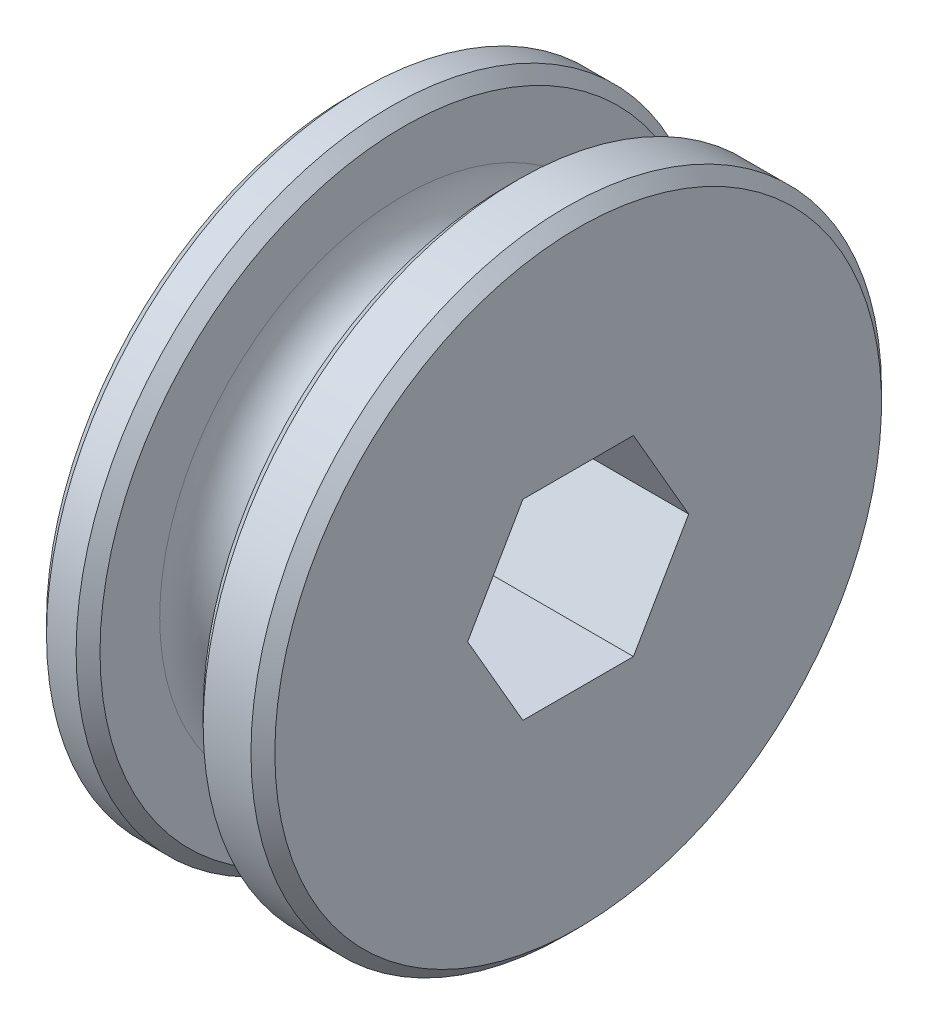
SolidWorks part; units mm, degrees
material "PET"
ref_plane "Front Plane" through (0, 0, 0) normal (0, 0, 1) x (1, 0, 0)
ref_plane "Top Plane" through (0, 0, 0) normal (0, 1, 0) x (1, 0, 0)
ref_plane "Right Plane" through (0, 0, 0) normal (1, 0, 0) x (0, 0, -1)
sketch "Sketch1" plane through (0, 0, 0) normal (0, 0, 1) x (1, 0, 0)
  line L0 (15.1765, 0) -> (0, 0)
  line L1 (0, 0) -> (15.1765, 0) construction
  line L2 (0, 0) -> (0, 20.955)
  line L3 (0, 20.955) -> (3.556, 20.955)
  line L4 (3.556, 16.1925) -> (3.556, 20.955)
  line L6 (10.414, 16.1925) -> (10.414, 20.955)
  line L7 (10.414, 20.955) -> (15.1765, 20.955)
  line L8 (15.1765, 0) -> (15.1765, 20.955)
  line L9 (6.985, 12.7635) -> (6.985, 0) construction
  arc A0 (3.556, 16.1925) -> (10.414, 16.1925) centre (6.985, 16.1925) ccw
  dimension "D1" = 3.429
  dimension "D2" = 4.7625
  dimension "D3" = 20.955
  dimension "D4" = 4.7625
  dimension "D5" = 3.556
  dimension "D7" = 12.7635
revolve "Revolve1" add sketch "Sketch1" angle 360 about L1
chamfer "Chamfer1" distance 0.7937 angle 45 1 edges at (0, 0, 20.955)
sketch "Sketch2" plane through (0, 0, 0) normal (-1, 0, 0) x (0, 0, 1)
  line L1 (3.6735, -6.3627) -> (7.347, 0)
  line L2 (7.347, 0) -> (3.6735, 6.3627)
  line L3 (3.6735, 6.3627) -> (-3.6735, 6.3627)
  line L4 (-3.6735, 6.3627) -> (-7.347, 0)
  line L5 (-7.347, 0) -> (-3.6735, -6.3627)
  line L6 (-3.6735, -6.3627) -> (3.6735, -6.3627)
  circle A0 centre (0, 0) radius 6.3627 construction
  dimension "D1" = 12.7254
extrude "Cut-Extrude1" cut sketch "Sketch2" against normal through all
chamfer "Chamfer2" distance 0.7937 angle 45 3 edges at (15.1765, 0, 20.955) (10.414, 0, 20.955) (3.556, 0, 20.955)
